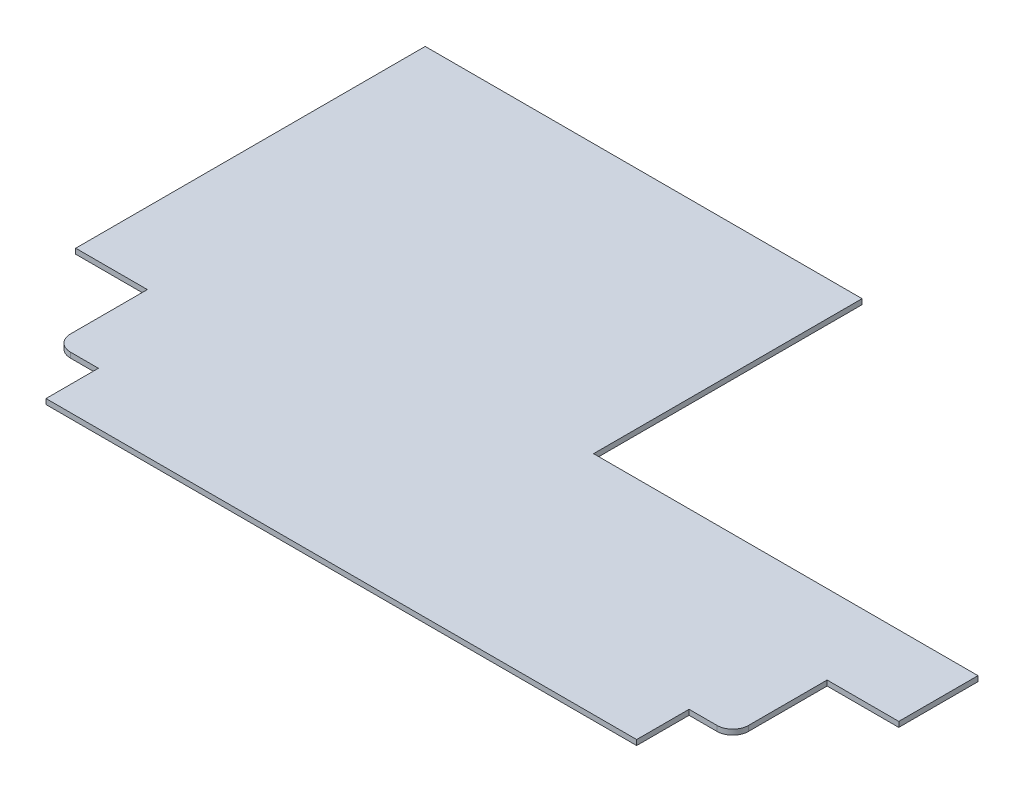
SolidWorks part; units mm, degrees
ref_plane "Alzado" through (0, 0, 0) normal (0, 0, 1) x (1, 0, 0)
ref_plane "Planta" through (0, 0, 0) normal (0, 1, 0) x (1, 0, 0)
ref_plane "Vista lateral" through (0, 0, 0) normal (1, 0, 0) x (0, 0, -1)
sketch "Croquis1" plane through (0, 0, 0) normal (0, 1, 0) x (1, 0, 0)
  line L1 (-125, 125) -> (125, 125)
  line L2 (-125, 125) -> (-125, -125)
  line L3 (-125, -125) -> (125, -125)
  line L4 (125, 125) -> (125, -125)
  line L5 (-125, 125) -> (125, -125) construction
  line L6 (-125, -125) -> (125, 125) construction
  point P0 (0, 0)
extrude "Saliente-Extruir1" add sketch "Croquis1" along normal blind 3
sketch "Croquis2" plane through (0, 3, 0) normal (0, 1, 0) x (1, 0, 0)
  line L0 (125, -125) -> (125, 125) construction
  line L1 (-125, 125) -> (125, 125)
  line L2 (-125, 125) -> (-125, 128)
  line L3 (-125, 128) -> (125, 128)
  line L4 (125, 125) -> (125, 128)
extrude "Saliente-Extruir2" add sketch "Croquis2" against normal blind 3
sketch "Croquis3" plane through (0, 3, 0) normal (0, 1, 0) x (1, 0, 0)
  line L1 (125, -125) -> (345, -125)
  line L2 (125, -125) -> (125, -25.66)
  line L3 (125, -25.66) -> (345, -25.66)
  line L4 (345, -125) -> (345, -25.66)
  dimension "D1" = 220
  dimension "D2" = 99.34
extrude "Saliente-Extruir4" add sketch "Croquis3" against normal blind 3
sketch "Croquis4" plane through (0, 3, 0) normal (0, 1, 0) x (1, 0, 0)
  line L1 (-125, -125) -> (-84, -125)
  line L2 (-125, -125) -> (-125, -73)
  line L3 (-125, -73) -> (-84, -73)
  line L4 (-84, -125) -> (-84, -73)
  dimension "D1" = 41
  dimension "D2" = 52
extrude "Cortar-Extruir1" cut sketch "Croquis4" against normal blind 3
sketch "Croquis5" plane through (0, 3, 0) normal (0, 1, 0) x (1, 0, 0)
  line L0 (-84, -125) -> (-75, -125) construction
  line L1 (-84, -125) -> (345, -125) construction
  line L2 (-75, -125) -> (-75, -116) construction
  line L3 (-84, -125) -> (-84, -73) construction
  line L4 (-84, -116) -> (-84, -125)
  line L5 (-84, -125) -> (-75, -125)
  arc A0 (-75, -125) -> (-84, -116) centre (-75, -116) cw
extrude "Cortar-Extruir2" cut sketch "Croquis5" against normal blind 3
sketch "Croquis6" plane through (0, 3, 0) normal (0, 1, 0) x (1, 0, 0)
  line L0 (-75, -125) -> (345, -125) construction
  line L1 (-59, -125) -> (280, -125)
  line L2 (-59, -125) -> (-59, -155)
  line L3 (-59, -155) -> (280, -155)
  line L4 (280, -125) -> (280, -155)
  line L5 (-125, 128) -> (-125, -73) construction
  line L6 (345, -125) -> (345, -25.66) construction
  dimension "D1" = 66
  dimension "D2" = 65
extrude "Saliente-Extruir5" add sketch "Croquis6" against normal blind 3
sketch "Croquis7" plane through (0, 3, 0) normal (0, 1, 0) x (1, 0, 0)
  line L0 (345, -72) -> (304, -72)
  line L1 (345, -125) -> (345, -25.66) construction
  line L2 (304, -125) -> (304, -116) construction
  line L3 (280, -125) -> (345, -125) construction
  line L4 (304, -116) -> (295, -116) construction
  line L5 (304, -116) -> (304, -72)
  line L6 (295, -125) -> (345, -125)
  line L7 (345, -125) -> (345, -72)
  line L8 (-59, -155) -> (280, -155) construction
  arc A0 (304, -116) -> (295, -125) centre (295, -116) cw
  dimension "D1" = 83
extrude "Cortar-Extruir3" cut sketch "Croquis7" against normal blind 3
sketch "Croquis8" plane through (0, 3, 0) normal (0, 1, 0) x (1, 0, 0)
  line L0 (-125, -73) -> (-125, -189.2013) construction
  line L1 (345, -72) -> (345, -206.9603) construction
  line L3 (280, -125) -> (279, -125)
  line L4 (280, -125) -> (280, -155)
  line L5 (280, -155) -> (279, -155)
  line L6 (279, -125) -> (279, -155)
extrude "Cortar-Extruir4" cut sketch "Croquis8" against normal blind 10
sketch "Croquis10" plane through (0, 3, 0) normal (0, 1, 0) x (1, 0, 0)
  line L1 (-84, -73) -> (-125, -73)
  line L2 (-84, -73) -> (-84, -72)
  line L3 (-84, -72) -> (-125, -72)
  line L4 (-125, -73) -> (-125, -72)
  line L8 (345, -72) -> (345, -25.66) construction
  line L9 (304, -72) -> (345, -72)
  line L10 (304, -72) -> (304, -71)
  line L11 (304, -71) -> (345, -71)
  line L12 (345, -72) -> (345, -71)
extrude "Cortar-Extruir5" cut sketch "Croquis10" against normal blind 3
